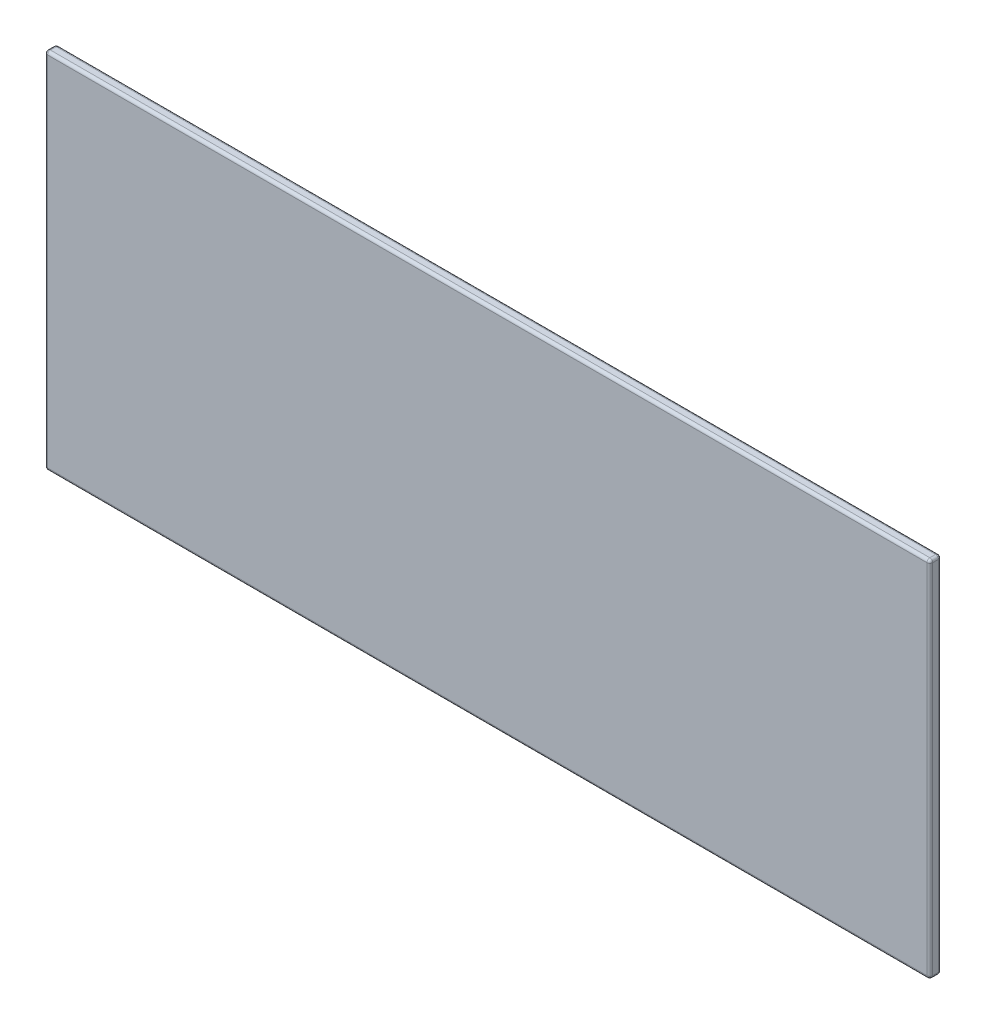
SolidWorks part; units mm, degrees
ref_plane "Front Plane" through (0, 0, 0) normal (0, 0, 1) x (1, 0, 0)
ref_plane "Top Plane" through (0, 0, 0) normal (0, 1, 0) x (1, 0, 0)
ref_plane "Right Plane" through (0, 0, 0) normal (1, 0, 0) x (0, 0, -1)
sketch "Sketch1" plane through (0, 0, 0) normal (0, 0, 1) x (1, 0, 0)
  line L1 (-77.35, -31.75) -> (77.35, -31.75)
  line L2 (-77.35, -31.75) -> (-77.35, 31.75)
  line L3 (-77.35, 31.75) -> (77.35, 31.75)
  line L4 (77.35, -31.75) -> (77.35, 31.75)
  line L5 (-77.35, -31.75) -> (77.35, 31.75) construction
  line L6 (-77.35, 31.75) -> (77.35, -31.75) construction
  point P0 (0, 0)
  dimension "D1" = 154.7
  dimension "D2" = 63.5
extrude "Boss-Extrude1" add sketch "Sketch1" along normal blind 2
fillet "Fillet1" radius 0.5 12 edges at (0, -31.75, 2) (0, -31.75, 0) (-77.35, 0, 2) (-77.35, -31.75, 1) (-77.35, 0, 0) (0, 31.75, 2) (-77.35, 31.75, 1) (0, 31.75, 0) (77.35, -31.75, 1) (77.35, 0, 2) (77.35, 31.75, 1) (77.35, 0, 0)
